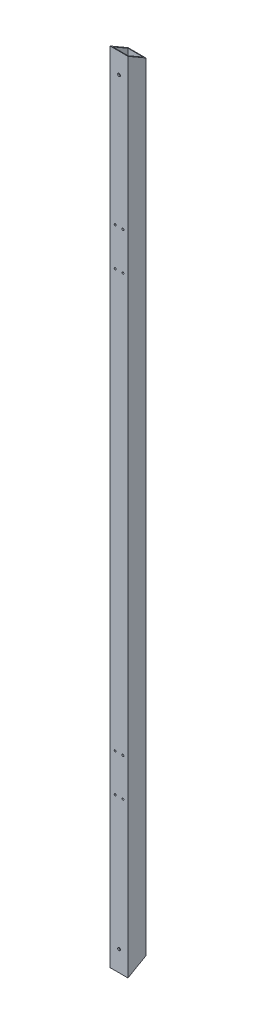
SolidWorks part; units mm, degrees
material "6061 Alloy"
ref_plane "Front Plane" through (0, 0, 0) normal (0, 0, 1) x (1, 0, 0)
ref_plane "Top Plane" through (0, 0, 0) normal (0, 1, 0) x (1, 0, 0)
ref_plane "Right Plane" through (0, 0, 0) normal (1, 0, 0) x (0, 0, -1)
sketch "Sketch1" plane through (0, 0, 0) normal (0, 0, 1) x (1, 0, 0)
  line L1 (-22.225, 990.092) -> (22.225, 990.092)
  line L2 (-22.225, 990.092) -> (-22.225, -990.092)
  line L3 (-22.225, -990.092) -> (22.225, -990.092)
  line L4 (22.225, 990.092) -> (22.225, -990.092)
  line L5 (-22.225, 990.092) -> (22.225, -990.092) construction
  line L6 (-22.225, -990.092) -> (22.225, 990.092) construction
  point P0 (0, 0)
  dimension "D1" = 44.45
  dimension "D2" = 1980.184
extrude "Boss-Extrude1" add sketch "Sketch1" along normal blind 44.45
sketch "Sketch2" plane through (0, 990.092, 0) normal (0, 1, 0) x (1, 0, 0)
  line L0 (22.225, 0) -> (-22.225, 0) construction
  line L1 (-19.05, -3.175) -> (19.05, -3.175)
  line L2 (-19.05, -3.175) -> (-19.05, -41.275)
  line L3 (-19.05, -41.275) -> (19.05, -41.275)
  line L4 (19.05, -3.175) -> (19.05, -41.275)
  line L5 (-19.05, -3.175) -> (19.05, -41.275) construction
  line L6 (-19.05, -41.275) -> (19.05, -3.175) construction
  line L7 (22.225, -44.45) -> (-22.225, -44.45) construction
  line L8 (-22.225, -44.45) -> (-22.225, 0) construction
  line L9 (22.225, -44.45) -> (22.225, 0) construction
  point P0 (0, -22.225)
  dimension "D1" = 3.175
  dimension "D2" = 3.175
  dimension "D3" = 3.175
  dimension "D4" = 3.175
extrude "Cut-Extrude1" cut sketch "Sketch2" against normal through all
sketch "Sketch3" plane through (22.225, 0, 0) normal (1, 0, 0) x (0, 0, -1)
  line L0 (-44.45, 990.092) -> (0, 964.4288)
  line L1 (0, -990.092) -> (0, 990.092) construction
  line L2 (0, 964.4288) -> (0, 990.092)
  line L3 (0, 990.092) -> (-44.45, 990.092)
  line L4 (-44.45, -990.092) -> (0, -964.4288)
  line L5 (0, -964.4288) -> (0, -990.092)
  line L6 (0, -990.092) -> (-44.45, -990.092)
  dimension "D1" = 60
  dimension "D2" = 60
extrude "Cut-Extrude2" cut sketch "Sketch3" against normal through all
ref_plane "Plane1" through (22.225, 964.4288, 0) normal (0, 1, 0) x (1, 0, 0)
sketch "Sketch13" plane through (0, 0, 44.45) normal (0, 0, 1) x (1, 0, 0)
  line L0 (-22.225, -990.092) -> (22.225, -990.092) construction
  line L1 (-22.225, 990.092) -> (-22.225, -990.092) construction
  line L2 (22.225, 990.092) -> (-22.225, 990.092) construction
  circle A0 centre (0, 939.038) radius 3.3734
  circle A1 centre (0, -939.038) radius 3.3734
  dimension "D1" = 6.7469
  dimension "D4" = 6.7469
  dimension "D2" = 51.054
  dimension "D3" = 22.225
  dimension "D5" = 22.225
  dimension "D6" = 51.054
extrude "Cut-Extrude7" cut sketch "Sketch13" against normal through all
sketch "Sketch15" plane through (0, 0, 44.45) normal (0, 0, 1) x (1, 0, 0)
  line L0 (-22.225, -990.092) -> (22.225, -990.092) construction
  line L5 (22.225, 990.092) -> (-22.225, 990.092) construction
  line L8 (-22.225, 990.092) -> (-22.225, -990.092) construction
  point P5 (-9.525, 518.1346)
  point P8 (9.525, 518.1346)
  point P11 (9.525, 612.1654)
  point P14 (-9.525, 612.1654)
  point P25 (-9.525, -612.1654)
  point P26 (9.525, -612.1654)
  point P27 (9.525, -518.1346)
  point P28 (-9.525, -518.1346)
  dimension "D1" = 94.0308
  dimension "D2" = 94.0308
  dimension "D3" = 377.9266
  dimension "D4" = 377.9266
  dimension "D5" = 12.7
  dimension "D6" = 31.75
hole_wizard "#10 (0.1935) Diameter Hole1" positions "3DSketch1" profile "Sketch16" hole size "#10" standard "ANSI Inch" end condition through all
sketch3d "3DSketch1"
  point P0 (-9.525, -612.1654, 44.45)
  point P3 (9.525, -612.1654, 44.45)
  point P6 (-9.525, -518.1346, 44.45)
  point P9 (9.525, -518.1346, 44.45)
  point P12 (-9.525, 518.1346, 44.45)
  point P15 (9.525, 518.1346, 44.45)
  point P18 (-9.525, 612.1654, 44.45)
  point P21 (9.525, 612.1654, 44.45)
sketch "Sketch16" plane through (-9.525, -612.1654, 44.45) normal (1, 0, 0) x (0, -1, 0)
  line L0 (0, 0) -> (0, 44.45)
  line L1 (0, 44.45) -> (2.4574, 44.45)
  line L2 (2.4574, 44.45) -> (2.4574, 0)
  line L5 (2.4574, 0) -> (0, 0)
  line L11 (0, -6.35) -> (0, 107.95) construction
  dimension "Thru Hole Dia." = 4.9149
  dimension "Thru Hole Depth" = 44.45
